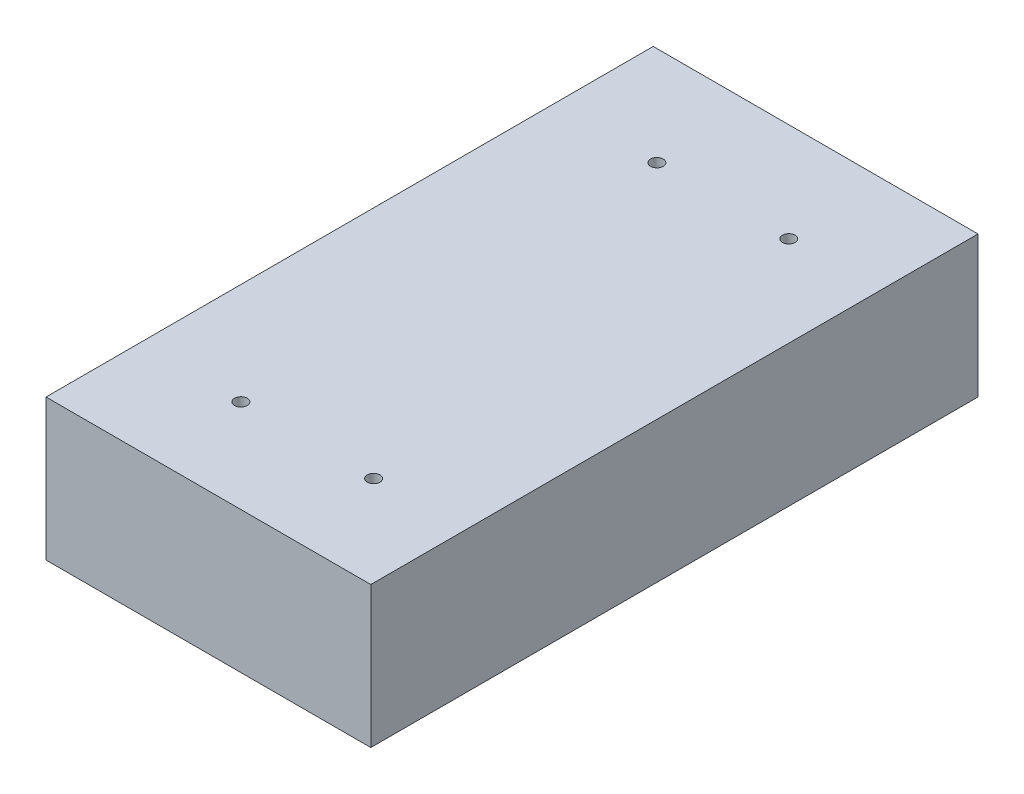
SolidWorks part; units mm, degrees
ref_plane "前视基准面" through (0, 0, 0) normal (0, 0, 1) x (1, 0, 0)
ref_plane "上视基准面" through (0, 0, 0) normal (0, 1, 0) x (1, 0, 0)
ref_plane "右视基准面" through (0, 0, 0) normal (1, 0, 0) x (0, 0, -1)
sketch "草图1" plane through (0, 0, 0) normal (0, 1, 0) x (1, 0, 0)
  line L1 (-57.5, -107.5) -> (57.5, -107.5)
  line L2 (-57.5, -107.5) -> (-57.5, 107.5)
  line L3 (-57.5, 107.5) -> (57.5, 107.5)
  line L4 (57.5, -107.5) -> (57.5, 107.5)
  line L5 (0, 107.5) -> (0, -107.5) construction
  line L6 (-57.5, 0) -> (57.5, 0) construction
  point P0 (0, 0)
  dimension "D1" = 115
  dimension "D2" = 215
extrude "凸台-拉伸1" add sketch "草图1" along normal blind 50
sketch "草图2" plane through (0, 0, 0) normal (0, -1, 0) x (1, 0, 0)
  line L0 (-57.5, 107.5) -> (57.5, 107.5) construction
  line L2 (57.5, 107.5) -> (57.5, -107.5) construction
  line L3 (63.1425, 0) -> (-62.9317, 0) construction
  line L4 (0, 115.9079) -> (0, -116.7911) construction
  circle A0 centre (25.5, 74.5) radius 2.25
  circle A5 centre (-21.5, 74.5) radius 2.25
  circle A6 centre (25.5, -72.5) radius 2.25
  circle A7 centre (-21.2, -72.5) radius 2.25
  dimension "D1" = 4.5
  dimension "D4" = 47
  dimension "D6" = 4.5
  dimension "D9" = 4.5
  dimension "D11" = 4.5
  dimension "D2" = 33
  dimension "D3" = 32
  dimension "D5" = 33
  dimension "D7" = 147
  dimension "D8" = 32
  dimension "D10" = 46.7
  dimension "D12" = 147
extrude "切除-拉伸1" cut sketch "草图2" against normal through all
